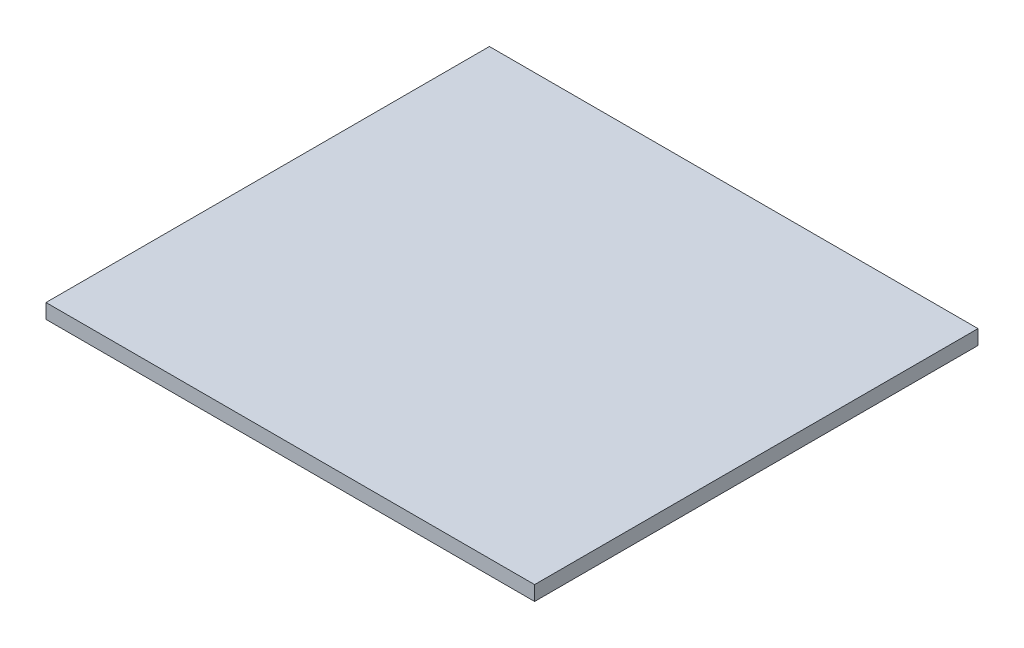
SolidWorks part; units mm, degrees
ref_plane "Alzado" through (0, 0, 0) normal (0, 0, 1) x (1, 0, 0)
ref_plane "Planta" through (0, 0, 0) normal (0, 1, 0) x (1, 0, 0)
ref_plane "Vista lateral" through (0, 0, 0) normal (1, 0, 0) x (0, 0, -1)
sketch "Croquis1" plane through (0, 0, 0) normal (0, 1, 0) x (1, 0, 0)
  line L1 (-222.6942, 98.6348) -> (177.3058, 98.6348)
  line L2 (-222.6942, 98.6348) -> (-222.6942, -264.3652)
  line L3 (-222.6942, -264.3652) -> (177.3058, -264.3652)
  line L4 (177.3058, 98.6348) -> (177.3058, -264.3652)
  dimension "D1" = 400
  dimension "D2" = 363
extrude "Saliente-Extruir1" add sketch "Croquis1" along normal blind 12
